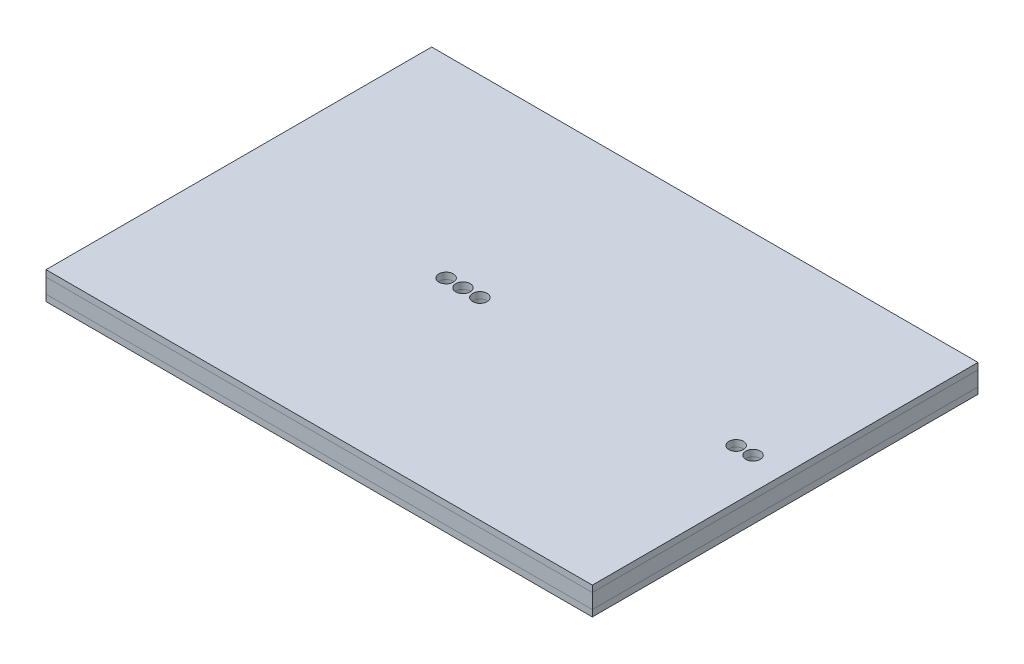
SolidWorks part; units mm, degrees
other "DetailItem21"
other "DetailItem22"
other "DetailItem23"
other "DetailItem24"
other "DetailItem25"
ref_plane "Front Plane" through (0, 0, 0) normal (0, 0, 1) x (1, 0, 0)
ref_plane "Top Plane" through (0, 0, 0) normal (0, 1, 0) x (1, 0, 0)
ref_plane "Right Plane" through (0, 0, 0) normal (1, 0, 0) x (0, 0, -1)
sketch "Sketch1" plane through (0, 0, 0) normal (0, 1, 0) x (1, 0, 0)
  line L1 (-85, 0) -> (85, 0)
  line L2 (-85, 0) -> (-85, 60)
  line L3 (-85, 60) -> (85, 60)
  line L4 (85, 0) -> (85, 60)
  dimension "D1" = 170
  dimension "D2" = 60
extrude "Boss-Extrude1" add sketch "Sketch1" along normal blind 2
sketch "Sketch2" plane through (0, 0, 0) normal (0, -1, 0) x (1, 0, 0)
  line L4 (-85, 0) -> (-85, -60)
  line L5 (-85, -60) -> (85, -60)
  line L6 (85, -60) -> (85, 0)
  line L7 (85, 0) -> (-85, 0)
  line L8 (-85, 0) -> (-85, -60)
  line L9 (-85, -60) -> (85, -60)
  line L10 (85, -60) -> (85, 0)
  line L11 (85, 0) -> (-85, 0)
  dimension "D1" = 0
extrude "Boss-Extrude2" add sketch "Sketch2" along normal blind 4.6 separate body
sketch "Sketch3" plane through (0, -4.6, 0) normal (0, -1, 0) x (1, 0, 0)
  line L4 (85, 0) -> (-85, 0)
  line L5 (-85, 0) -> (-85, -60)
  line L6 (-85, -60) -> (85, -60)
  line L7 (85, -60) -> (85, 0)
  line L8 (85, 0) -> (-85, 0)
  line L9 (-85, 0) -> (-85, -60)
  line L10 (-85, -60) -> (85, -60)
  line L11 (85, -60) -> (85, 0)
  dimension "D1" = 0
extrude "Boss-Extrude3" add sketch "Sketch3" along normal blind 2 separate body
sketch "Sketch4" plane through (0, 2, 0) normal (0, 1, 0) x (1, 0, 0)
  line L0 (-85, 0) -> (85, 0) construction
  line L1 (85, 0) -> (85, 60) construction
  circle A0 centre (75, 0) radius 2.25
  circle A1 centre (-10, 0) radius 2.25
  circle A2 centre (69.75, 0) radius 2.25
  circle A3 centre (-15.25, 0) radius 2.25
  point P6 (0, 0)
  dimension "D3" = 4.5
  dimension "D4" = 4.5
  dimension "D5" = 4.5
  dimension "D6" = 4.5
  dimension "D7" = 0.75
  dimension "D8" = 0.75
  dimension "D1" = 10
  dimension "D2" = 10
extrude "Cut-Extrude1" cut sketch "Sketch4" against normal through all
hole_wizard "Ø4.5 (4.5) Diameter Hole1" positions "Sketch6" profile "Sketch8" hole size "Ø4.5" standard "ISO" end condition through all
sketch "Sketch6" plane through (0, 2, 0) normal (0, 1, 0) x (1, 0, 0)
  line L0 (-85, 0) -> (-17.5, 0) construction
  point P0 (-20.5, 0)
  dimension "D1" = 3
sketch "Sketch8" plane through (-20.5, 2, 0) normal (1, 0, 0) x (0, 0, 1)
  line L0 (0, 0) -> (0, 8.6)
  line L1 (0, 8.6) -> (2.25, 8.6)
  line L2 (2.25, 8.6) -> (2.25, 0)
  line L5 (2.25, 0) -> (0, 0)
  line L11 (0, -6.35) -> (0, 107.95) construction
  dimension "Thru Hole Dia." = 4.5
  dimension "Thru Hole Depth" = 8.6
mirror "Mirror1" about plane through (85, -4.6, 0) normal (0, 0, -1) of bodies 107 108 109
